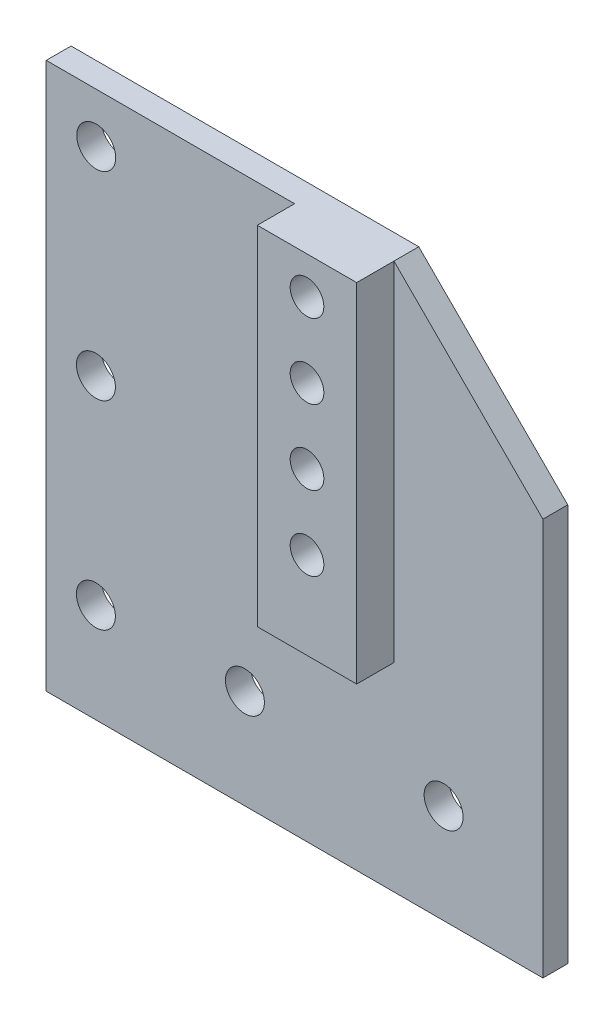
SolidWorks part; units mm, degrees
ref_plane "Front Plane" through (0, 0, 0) normal (0, 0, 1) x (1, 0, 0)
ref_plane "Top Plane" through (0, 0, 0) normal (0, 1, 0) x (1, 0, 0)
ref_plane "Right Plane" through (0, 0, 0) normal (1, 0, 0) x (0, 0, -1)
sketch "Sketch1" plane through (0, 0, 0) normal (0, 0, 1) x (1, 0, 0)
  line L0 (-254, -12.7) -> (-266.7, -12.7)
  line L2 (-266.7, 57.15) -> (-254, 57.15)
  line L3 (-254, -16.7024) -> (-254, 609.6) construction
  line L4 (-254, -12.7) -> (-203.2, -12.7)
  line L5 (-254, 57.15) -> (-222.25, 57.15)
  line L6 (-203.2, -12.7) -> (-203.2, 12.7)
  line L7 (-254, 12.7) -> (254, 12.7) construction
  line L13 (-222.25, 57.15) -> (-203.2, 38.1)
  line L15 (-266.7, -12.7) -> (-266.7, 57.15)
  line L16 (-266.7, 609.6) -> (-266.7, -16.7024) construction
  line L17 (-203.2, 12.7) -> (-203.2, 38.1)
  dimension "D1" = 69.85
  dimension "D2" = 25.4
  dimension "D3" = 31.75
extrude "Boss-Extrude1" add sketch "Sketch1" along normal blind 3.175
sketch "Sketch2" plane through (0, 0, 3.175) normal (0, 0, 1) x (1, 0, 0)
  line L0 (-203.2, -12.7) -> (-203.2, 12.7) construction
  line L1 (-215.9, 0) -> (-241.3, 0) construction
  line L2 (-203.2, 0) -> (-215.9, 0) construction
  line L3 (-254, -12.7) -> (-266.7, -12.7) construction
  line L4 (-260.35, -12.7) -> (-260.35, 0) construction
  line L5 (-260.35, 0) -> (-260.35, 25.4) construction
  line L6 (-260.35, 25.4) -> (-260.3118, 50.7989) construction
  line L7 (-260.3118, 25.4) -> (-260.3118, 51.0017) construction
  line L8 (-254, 12.7) -> (254, 12.7) construction
  point P14 (0, 0)
  dimension "D1" = 12.7
  dimension "D2" = 25.4
  dimension "D3" = 12.7
  dimension "D4" = 25.4
  dimension "D5" = 25.3989
hole_wizard "#10 Clearance Hole1" positions "Sketch3" profile "Sketch4" hole size "#10" standard "ANSI Inch" end condition through all
sketch "Sketch3" plane through (0, 0, 3.175) normal (0, 0, 1) x (1, 0, 0)
  point P15 (-260.3118, 50.7989)
  point P18 (-260.35, 25.4)
  point P21 (-260.35, 0)
  point P24 (-241.3, 0)
  point P27 (-215.9, 0)
sketch "Sketch4" plane through (-260.3118, 50.7989, 3.175) normal (1, 0, 0) x (0, -1, 0)
  line L0 (0, 0) -> (0, 3.175)
  line L1 (0, 3.175) -> (2.4892, 3.175)
  line L2 (2.4892, 3.175) -> (2.4892, 0)
  line L5 (2.4892, 0) -> (0, 0)
  line L11 (0, -6.35) -> (0, 107.95) construction
  dimension "Thru Hole Dia." = 4.9784
  dimension "Thru Hole Depth" = 3.175
sketch "Sketch5" plane through (0, 0, 3.175) normal (0, 0, 1) x (1, 0, 0)
  line L0 (-222.25, 57.15) -> (-222.25, 50.8) construction
  line L1 (-222.25, 57.15) -> (-234.95, 57.15)
  line L3 (-234.95, 57.15) -> (-234.95, 12.7)
  line L4 (-222.25, 50.8) -> (-222.25, 12.7)
  line L5 (-222.25, 12.7) -> (-234.95, 12.7)
  line L6 (-222.25, 50.8) -> (-222.25, 57.15)
  line L7 (-222.25, 57.15) -> (-266.7, 57.15) construction
  point P7 (-222.25, 50.8)
  dimension "D3" = 38.1
extrude "Boss-Extrude2" add sketch "Sketch5" along normal blind 4.7625
sketch "Sketch6" plane through (0, 0, 7.9375) normal (0, 0, 1) x (1, 0, 0)
  line L0 (-228.6, 57.15) -> (-228.6, 52.3875) construction
  line L1 (-228.6, 52.3875) -> (-228.6, 42.8625) construction
  line L2 (-228.6, 42.8625) -> (-228.6, 33.3375) construction
  line L3 (-222.25, 57.15) -> (-234.95, 57.15) construction
  line L4 (-228.6, 33.3375) -> (-228.6, 23.8125) construction
  dimension "D1" = 9.525
  dimension "D2" = 4.7625
  dimension "D3" = 9.525
  dimension "D4" = 9.525
hole_wizard "#8 Clearance Hole1" positions "Sketch7" profile "Sketch8" hole size "#8" standard "ANSI Inch" end condition through all
sketch "Sketch7" plane through (0, 0, 7.9375) normal (0, 0, 1) x (1, 0, 0)
  point P0 (-228.6, 42.8625)
  point P3 (-228.6, 52.3875)
  point P7 (-228.6, 33.3375)
  point P10 (-228.6, 23.8125)
sketch "Sketch8" plane through (-228.6, 42.8625, 7.9375) normal (1, 0, 0) x (0, -1, 0)
  line L0 (0, 0) -> (0, 7.9375)
  line L1 (0, 7.9375) -> (2.1526, 7.9375)
  line L2 (2.1526, 7.9375) -> (2.1526, 0)
  line L5 (2.1526, 0) -> (0, 0)
  line L11 (0, -6.35) -> (0, 107.95) construction
  dimension "Thru Hole Dia." = 4.3053
  dimension "Thru Hole Depth" = 7.9375
